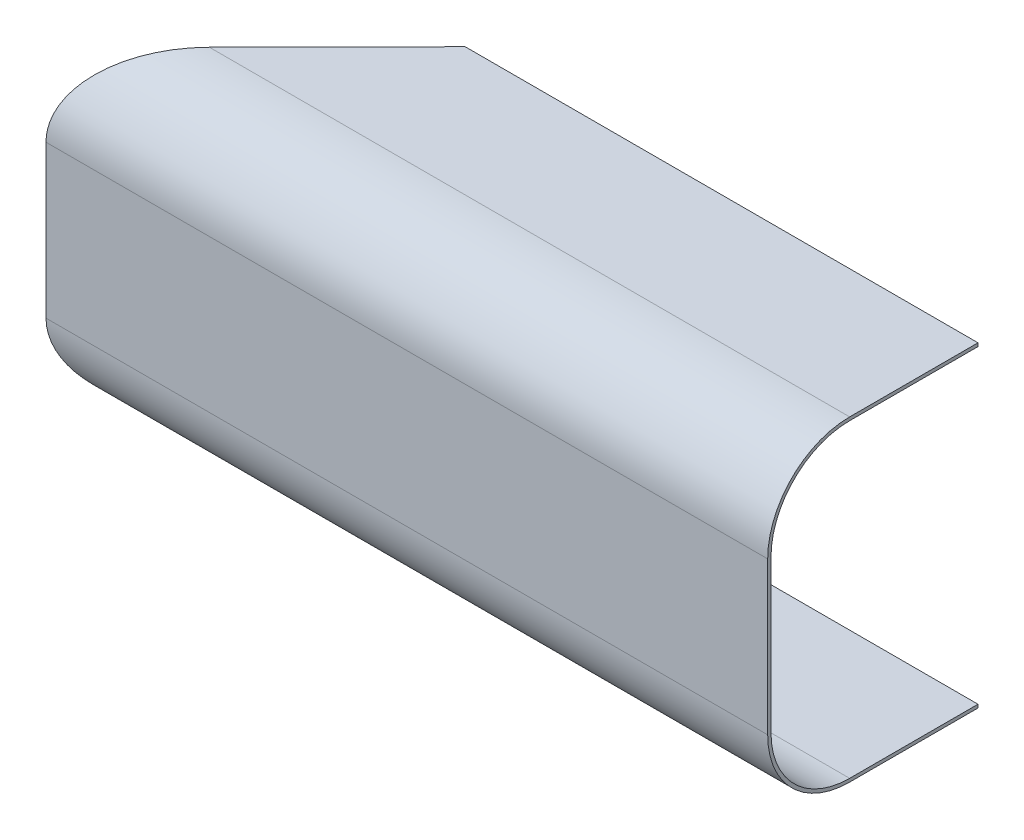
SolidWorks part; units mm, degrees
ref_plane "Front Plane" through (0, 0, 0) normal (0, 0, 1) x (1, 0, 0)
ref_plane "Top Plane" through (0, 0, 0) normal (0, 1, 0) x (1, 0, 0)
ref_plane "Right Plane" through (0, 0, 0) normal (1, 0, 0) x (0, 0, -1)
sketch "Sketch1" plane through (0, 0, -24.4767) normal (1, 0, 0) x (0, 0, -1)
  line L0 (19.05, 118.745) -> (-30.1625, 118.745)
  line L1 (-60.325, 88.5825) -> (-60.325, 30.1625)
  line L2 (-30.1625, 0) -> (19.05, 0)
  line L3 (19.05, 120.015) -> (-30.1625, 120.015)
  line L4 (-61.595, 88.5825) -> (-61.595, 30.1625)
  line L5 (-30.1625, -1.27) -> (19.05, -1.27)
  line L6 (19.05, 120.015) -> (19.05, 118.745)
  line L7 (19.05, 0) -> (19.05, -1.27)
  arc A0 (-30.1625, 118.745) -> (-60.325, 88.5825) centre (-30.1625, 88.5825) ccw
  arc A1 (-60.325, 30.1625) -> (-30.1625, 0) centre (-30.1625, 30.1625) ccw
  arc A2 (-30.1625, 120.015) -> (-61.595, 88.5825) centre (-30.1625, 88.5825) ccw
  arc A3 (-61.595, 30.1625) -> (-30.1625, -1.27) centre (-30.1625, 30.1625) ccw
  point P16 (0, 0)
extrude "Boss-Extrude1" add sketch "Sketch1" along normal blind 196.85 and the other way blind 80.01
sketch "Sketch2" plane through (0, 0, 0) normal (0, 1, 0) x (1, 0, 0)
  line L0 (0.2102, 43.5267) -> (-120.9884, -78.5308)
  line L1 (-80.01, 43.5267) -> (196.85, 43.5267) construction
  line L2 (-19.05, 24.2665) -> (0, 43.3165) construction
  line L3 (-120.9884, -78.5308) -> (-120.9884, 43.5267)
  line L4 (-120.9884, 43.5267) -> (0.2102, 43.5267)
  point P6 (-109.7831, -30.6433)
  point P8 (-83.2709, -36.7874)
  point P9 (-79.618, -36.1263)
  point P10 (-79.8016, -37.0521)
  point P11 (-120.9884, 43.5267)
extrude "Cut-Extrude1" cut sketch "Sketch2" against normal blind 196.85 and the other way blind 196.85 contours L3 L4 L0
